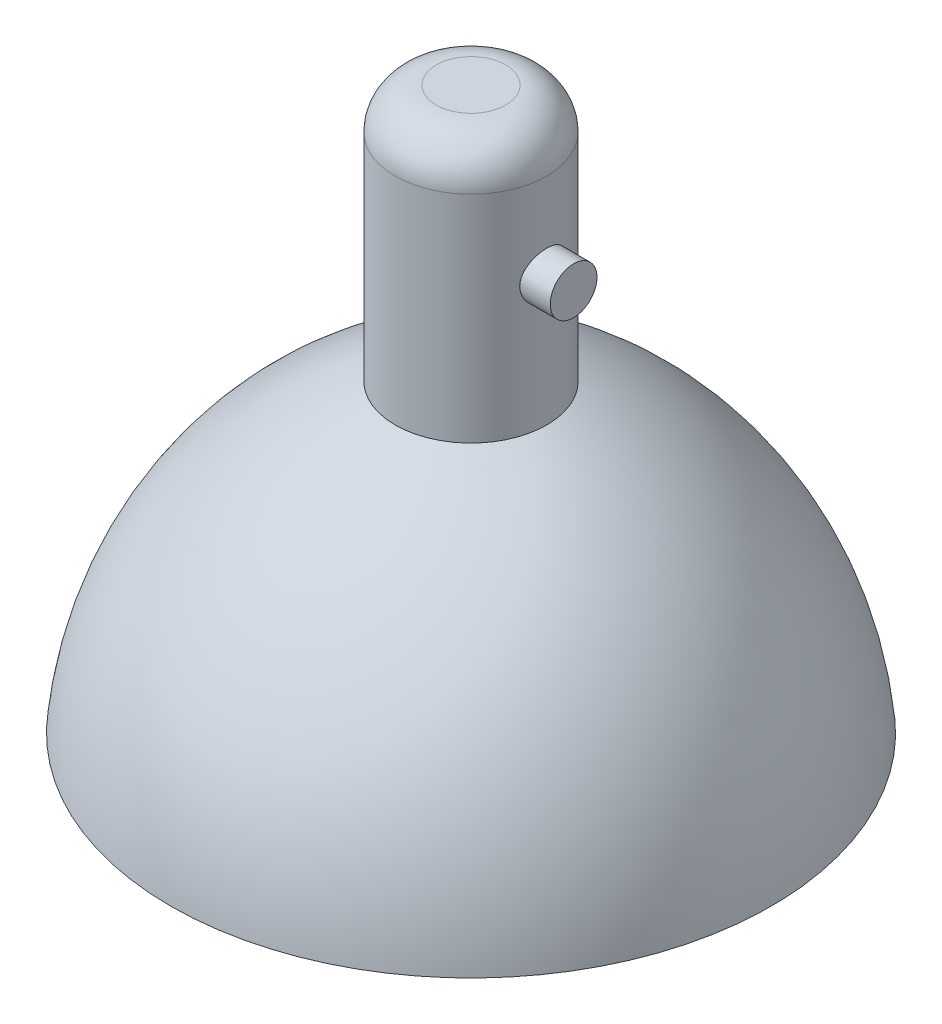
SolidWorks part; units mm, degrees
ref_plane "Front" through (0, 0, 0) normal (0, 0, 1) x (1, 0, 0)
ref_plane "Top" through (0, 0, 0) normal (0, 1, 0) x (1, 0, 0)
ref_plane "Right" through (0, 0, 0) normal (1, 0, 0) x (0, 0, -1)
sketch "草图2" plane through (0, 0, 0) normal (0, 0, 1) x (1, 0, 0)
  line L0 (0, 0) -> (29.2534, 0)
  line L1 (0, 0) -> (0, 29.676)
  line L2 (0, 29.676) -> (7.3853, 29.676)
  arc A0 (7.3853, 29.676) -> (29.2534, 0) centre (-6.2806, -3.2896) cw
revolve "旋转1" add sketch "草图2" angle 360 about L1
shell "抽壳1" thickness 2
sketch "草图4" plane through (0, 29.676, 0) normal (0, 1, 0) x (1, 0, 0)
  circle A0 centre (0, 0) radius 7.3853
extrude "凸台-拉伸1" add sketch "草图4" along normal blind 25
fillet "圆角1" radius 4 1 edges at (0, 54.676, 7.3853)
sketch "草图5" plane through (0, 0, 0) normal (1, 0, 0) x (0, 0, -1)
  circle A0 centre (0, 42.3153) radius 2.2777
extrude "凸台-拉伸2" add sketch "草图5" along normal blind 10
